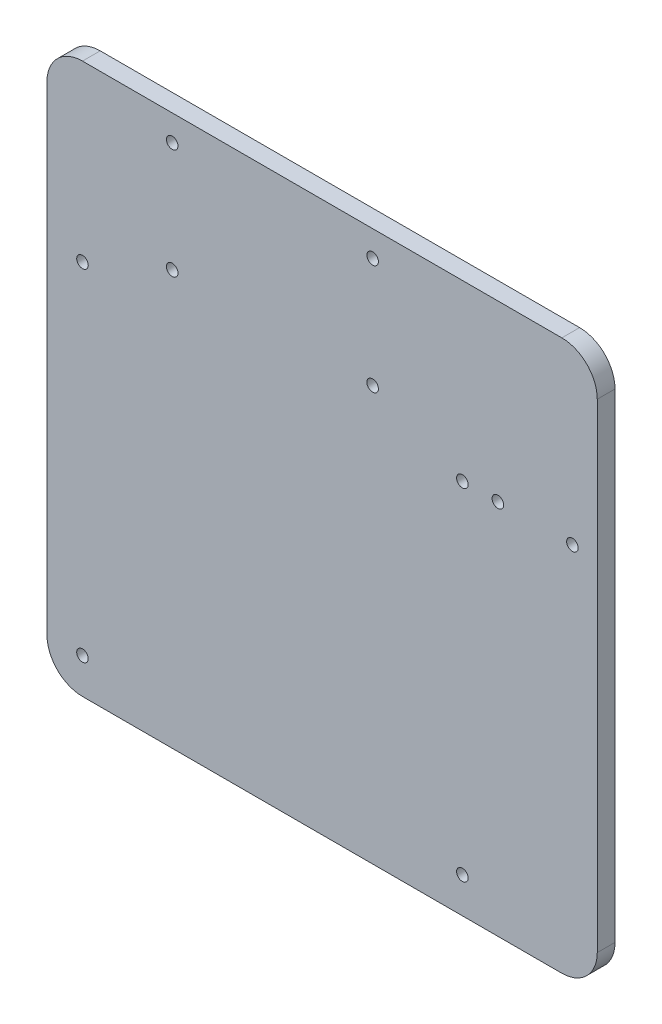
SolidWorks part; units mm, degrees
ref_plane "Front Plane" through (0, 0, 0) normal (0, 0, 1) x (1, 0, 0)
ref_plane "Top Plane" through (0, 0, 0) normal (0, 1, 0) x (1, 0, 0)
ref_plane "Right Plane" through (0, 0, 0) normal (1, 0, 0) x (0, 0, -1)
sketch "Sketch1" plane through (0, 0, 0) normal (0, 0, 1) x (1, 0, 0)
  line L0 (-75, -75) -> (-75, -65) construction
  line L2 (-75, 75) -> (-75, -75)
  line L3 (-75, -75) -> (75, -75)
  line L5 (-65, 65) -> (75, -75) construction
  line L6 (-75, -75) -> (75, 75) construction
  line L7 (-75, -65) -> (65, -65) construction
  line L8 (-75, -75) -> (-65, -75) construction
  line L9 (-65, -75) -> (-65, 75) construction
  line L10 (-65, -65) -> (-65, 31) construction
  line L11 (-65, -65) -> (42, -65) construction
  line L12 (42, -65) -> (42, 31) construction
  line L13 (42, 31) -> (52, 31) construction
  line L14 (52, 31) -> (73, 31) construction
  line L15 (-65, 31) -> (42, 31) construction
  line L16 (-11.5, 57.2212) -> (-11.5, 75) construction
  line L18 (-75, 75) -> (-75, 80)
  line L25 (-75, 80) -> (75, 80)
  line L26 (75, 80) -> (80, 80)
  line L27 (80, 80) -> (80, -75)
  line L28 (80, -75) -> (75, -75)
  circle A0 centre (-65, -65) radius 1.625
  circle A1 centre (-65, 31) radius 1.625
  circle A2 centre (42, 31) radius 1.625
  circle A3 centre (42, -65) radius 1.625
  circle A4 centre (52, 31) radius 1.625
  circle A5 centre (73, 31) radius 1.625
  circle A6 centre (-39.7281, 72.7212) radius 1.625
  circle A7 centre (-39.7281, 41.7212) radius 1.625
  circle A8 centre (16.7281, 41.7212) radius 1.625
  circle A9 centre (16.7281, 72.7212) radius 1.625
  point P0 (0, 0)
extrude "Boss-Extrude1" add sketch "Sketch1" along normal blind 5
sketch "Sketch2" plane through (0, 0, 5) normal (0, 0, 1) x (1, 0, 0)
  line L0 (-75, 70.0056) -> (-75, 80)
  line L1 (-75, 80) -> (-65.0056, 80)
  line L2 (70.0245, 80) -> (80, 80)
  line L3 (80, 80) -> (80, 70.0245)
  line L4 (69.9698, -75) -> (80, -75)
  line L5 (80, -75) -> (80, -64.9698)
  line L6 (-75, -65) -> (-75, -75)
  line L7 (-75, -75) -> (-65, -75)
  arc A0 (-75, -65) -> (-65, -75) centre (-65, -65) ccw
  arc A1 (69.9698, -75) -> (80, -64.9698) centre (69.9698, -64.9698) ccw
  arc A2 (80, 70.0245) -> (70.0245, 80) centre (70.0245, 70.0245) ccw
  arc A3 (-65.0056, 80) -> (-75, 70.0056) centre (-65.0056, 70.0056) ccw
extrude "Cut-Extrude1" cut sketch "Sketch2" against normal blind 5
